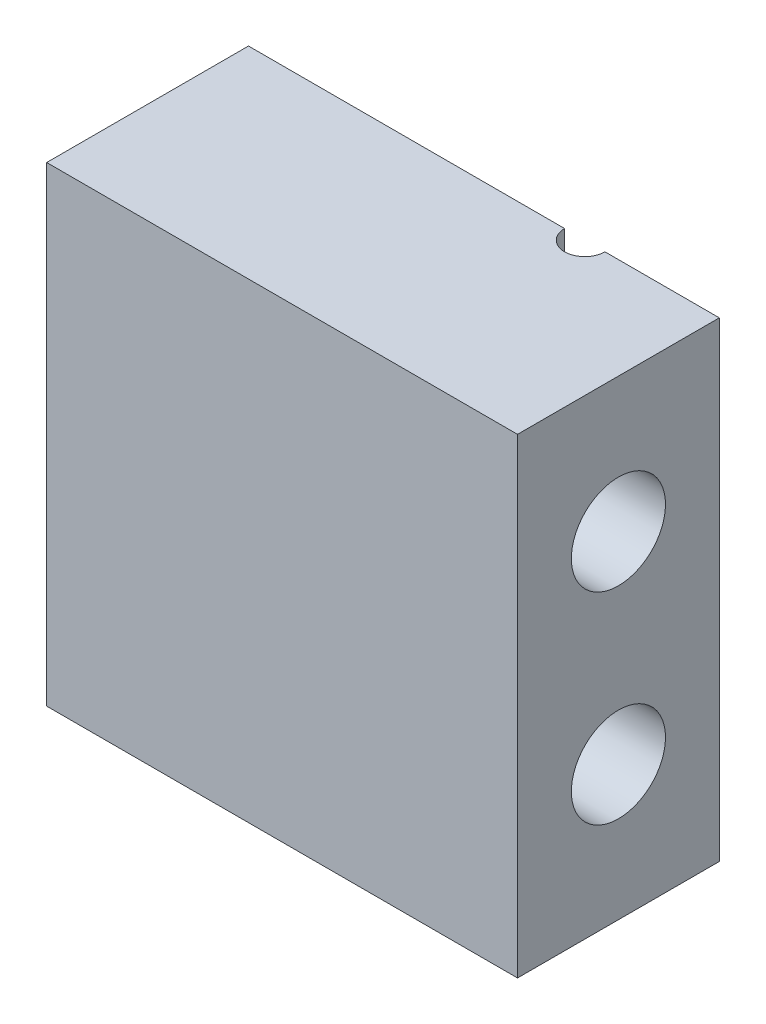
SolidWorks part; units mm, degrees
ref_plane "Front Plane" through (0, 0, 0) normal (0, 0, 1) x (1, 0, 0)
ref_plane "Top Plane" through (0, 0, 0) normal (0, 1, 0) x (1, 0, 0)
ref_plane "Right Plane" through (0, 0, 0) normal (1, 0, 0) x (0, 0, -1)
sketch "Sketch1" plane through (0, 0, 0) normal (0, 1, 0) x (1, 0, 0)
  line L0 (6.731, 3.81) -> (8.89, 3.81)
  line L1 (0, 0) -> (8.89, 0)
  line L2 (0, 0) -> (0, 3.81)
  line L3 (0, 3.81) -> (5.969, 3.81)
  line L4 (8.89, 0) -> (8.89, 3.81)
  arc A1 (5.969, 3.81) -> (6.731, 3.81) centre (6.35, 3.81) ccw
  dimension "D2" = 0.762
  dimension "D1" = 8.89
  dimension "D3" = 2.54
  dimension "D4" = 3.81
extrude "Boss-Extrude1" add sketch "Sketch1" along normal blind 8.89
hole_wizard "#2-56 Tapped Hole1" positions "3DSketch2" profile "Sketch12" tap size "#2-56" standard "ANSI Inch"
sketch3d "3DSketch2"
  line L1 (8.89, 8.89, 0) -> (8.89, 0, 0) construction
  line L2 (8.89, 8.89, 0) -> (8.89, 8.89, -3.81) construction
  line L3 (5.969, 0, -3.81) -> (0, 0, -3.81) construction
  line L4 (0, 8.89, -3.81) -> (0, 0, -3.81) construction
  point P0 (8.89, 2.54, -1.905)
  point P2 (8.89, 6.35, -1.905)
  point P18 (2.032, 2.54, -3.81)
  point P20 (2.032, 6.35, -3.81)
  point P23 (0, 0, 0)
  dimension "D2" = 1.905
  dimension "D3" = 2.54
  dimension "D6" = 3.81
  dimension "D1" = 3.81
  dimension "D4" = 2.54
  dimension "D5" = 2.032
sketch "Sketch12" plane through (8.89, 2.54, -1.905) normal (0, 1, 0) x (0, 0, -1)
  line L0 (0, 0) -> (0, 3.0742)
  line L1 (0, 3.0742) -> (0.889, 2.54)
  line L2 (0.889, 2.54) -> (0.889, 0)
  line L5 (0.889, 0) -> (0, 0)
  line L10 (0, 3.0742) -> (-0.889, 2.54) construction
  line L11 (0, -6.35) -> (0, 107.95) construction
  dimension "Tap Drill Dia." = 1.778
  dimension "Tap Drill Depth" = 2.54
  dimension "Drill Angle" = 118
cosmetic thread "Hole Thread4"
cosmetic thread "Hole Thread5"
cosmetic thread "Hole Thread6"
cosmetic thread "Hole Thread7"
equation "\"D2@3DSketch2\"=0.15/2"
